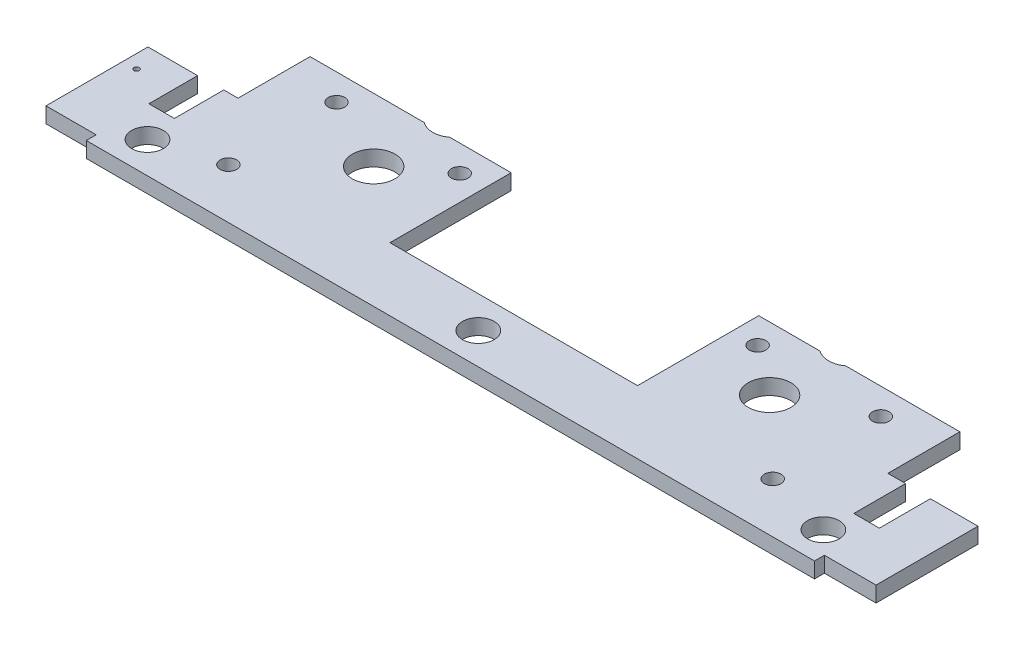
SolidWorks part; units mm, degrees
material "Copper"
ref_plane "Front Plane" through (0, 0, 0) normal (0, 0, 1) x (1, 0, 0)
ref_plane "Top Plane" through (0, 0, 0) normal (0, 1, 0) x (1, 0, 0)
ref_plane "Right Plane" through (0, 0, 0) normal (1, 0, 0) x (0, 0, -1)
sketch "Sketch1" plane through (0, 0, 0) normal (0, 1, 0) x (1, 0, 0)
  line L0 (44.3513, -40.0144) -> (37.1363, -40.0144)
  line L1 (0, 0) -> (0, -46.6159) construction
  line L2 (-19.6486, -28.7674) -> (44.3513, -28.7674) construction
  line L3 (-36.4337, -40.0144) -> (-36.4337, -46.6159)
  line L4 (37.1363, -40.0144) -> (37.1363, -46.6159)
  line L5 (-36.4337, -40.0144) -> (-43.6487, -40.0144)
  line L6 (-32.4727, -10.3704) -> (-32.4727, -29.6479)
  line L7 (-32.4727, 38.1938) -> (-32.4727, -29.6479) construction
  line L8 (-19.6486, -20.6394) -> (46.7444, -20.6394) construction
  line L9 (-42.3787, -29.6159) -> (-32.4727, -29.6479)
  line L10 (-12.1556, -10.3704) -> (-32.4727, -10.3704)
  line L11 (29.9683, -46.6159) -> (37.1363, -46.6159)
  line L12 (44.3513, -40.0144) -> (44.3513, -31.6519)
  line L13 (42.3513, -29.6159) -> (38.7463, -29.6159)
  line L14 (38.7463, -29.6159) -> (33.1753, -29.6479)
  line L15 (-11.5577, -34.6159) -> (-12.1556, -34.6159)
  line L16 (-12.1556, -34.6159) -> (-12.1556, -10.3704)
  line L17 (33.1753, -29.6479) -> (33.1753, 37.3661) construction
  line L18 (33.1753, -12.9294) -> (33.1753, -29.6479)
  line L19 (12.8581, -10.3704) -> (33.1753, -10.3704)
  line L20 (33.1753, -10.3704) -> (33.1753, -12.9294)
  line L21 (-43.6487, -29.6479) -> (-43.6487, -44.6339) construction
  line L22 (-43.6487, -30.8859) -> (-43.6487, -40.0144)
  line L23 (-36.4337, -46.6159) -> (-30.0837, -46.6159)
  line L24 (-30.0837, -46.6159) -> (29.9683, -46.6159)
  line L25 (-11.5577, -34.6159) -> (12.2603, -34.6159)
  line L26 (-19.6486, -28.7674) -> (-19.6486, -3.6898) construction
  line L27 (-19.6486, -3.6898) -> (-12.1556, -3.6898) construction
  line L28 (-43.6487, -30.8859) -> (-43.6487, -29.6479)
  line L29 (-43.6487, -29.6479) -> (-42.3787, -29.6159)
  line L30 (44.3513, -31.6519) -> (44.3513, -29.6159)
  line L31 (44.3513, -29.6159) -> (42.3513, -29.6159)
  line L32 (12.2603, -34.6159) -> (12.8581, -34.6159)
  line L33 (12.8581, -34.6159) -> (12.8581, -10.3704)
  circle A2 centre (-19.6486, -28.7674) radius 2.159
  circle A3 centre (-19.6486, -20.6394) radius 2.159
  circle A4 centre (20.3514, -20.6394) radius 2.159
  circle A5 centre (20.3514, -28.7674) radius 2.159
  dimension "D2" = 7.493
  dimension "D8" = 4.318
  dimension "D3" = 4.318
  dimension "D6" = 4.318
  dimension "D9" = 4.318
  dimension "D10" = 8.128
  dimension "D1" = 12
  dimension "D4" = 0
  dimension "D11" = 8.128
  dimension "D12" = 0
extrude "Boss-Extrude1" add sketch "Sketch1" along normal blind 1.575
sketch "Sketch2" plane through (0, 0, 0) normal (0, -1, 0) x (1, 0, 0)
  line L2 (-49.1064, 40.0144) -> (44.3513, 40.0144)
  line L4 (-49.1064, 40.0144) -> (-49.1064, 46.6164)
  line L6 (-49.1064, 46.6164) -> (44.3513, 46.6164)
  line L7 (44.3513, 40.0144) -> (44.3513, 46.6164)
  line L10 (-49.1064, 40.0144) -> (44.3513, 46.6164) construction
  line L12 (-49.1064, 46.6164) -> (44.3513, 40.0144) construction
  point P0 (-2.3775, 43.3154)
  dimension "D1" = 6.602
extrude "Cut-Extrude1" cut sketch "Sketch2" against normal through all
sketch "Sketch3" plane through (0, 0, 0) normal (0, -1, 0) x (1, 0, 0)
  line L0 (-41.5047, 40.0144) -> (-41.5047, 29.6188)
  line L1 (-43.6487, 40.0144) -> (44.3513, 40.0144) construction
  line L3 (-32.4727, 29.6479) -> (-42.3787, 29.6159) construction
  line L4 (-41.5047, 29.6188) -> (-34.6297, 29.641)
  line L8 (-41.5047, 40.0144) -> (-48.1288, 40.0144)
  line L9 (-48.1288, 40.0144) -> (-48.1288, 8.9761)
  line L10 (-48.1288, 8.9761) -> (-34.6297, 8.9761)
  line L11 (-34.6297, 29.641) -> (-34.6297, 8.9761)
  dimension "D1" = 6.6241
  dimension "D2" = 6.875
  dimension "D3" = 31.0383
  dimension "D4" = 20.6649
  dimension "D5" = 10.3956
extrude "Cut-Extrude2" cut sketch "Sketch3" against normal through all
sketch "Sketch4" plane through (0, 0, 0) normal (0, -1, 0) x (1, 0, 0)
  line L0 (42.3513, 40.0144) -> (42.3513, 32.4201)
  line L1 (35.4763, 29.6159) -> (35.4763, 10.3704)
  line L2 (35.4763, 10.3704) -> (54.7109, 10.3704)
  line L7 (54.7109, 10.3704) -> (54.7109, 40.0144)
  line L8 (-41.5047, 40.0144) -> (44.3513, 40.0144) construction
  line L11 (44.3513, 40.0144) -> (44.3513, 29.6159) construction
  line L12 (42.3513, 32.4201) -> (42.3513, 29.6159)
  line L13 (44.3513, 29.6159) -> (38.7463, 29.6159) construction
  line L14 (42.3513, 29.6159) -> (35.4763, 29.6159)
  line L15 (42.3513, 40.0144) -> (54.7109, 40.0144)
  dimension "D2" = 2
extrude "Cut-Extrude3" cut sketch "Sketch4" against normal through all
sketch "Sketch6" plane through (0, 0, 0) normal (0, -1, 0) x (-1, 0, 0)
  circle A0 centre (27.1416, -35.9479) radius 0.8382
  circle A1 centre (27.1416, -25.0259) radius 0.8382
  circle A2 centre (14.6956, -25.0259) radius 0.8382
  circle A3 centre (-15.3981, -25.0259) radius 0.8382
  circle A4 centre (-27.8444, -25.0259) radius 0.8382
  circle A5 centre (-27.8444, -35.9479) radius 0.8382
extrude "Cut-Extrude4" cut sketch "Sketch6" against normal blind 2.54
sketch "Sketch7" plane through (0, 0, 0) normal (0, -1, 0) x (1, 0, 0)
  line L0 (-32.4727, 10.3704) -> (-32.4727, 29.6479) construction
  line L1 (-32.4727, 22.3704) -> (33.1753, 22.3704)
  line L2 (-32.4727, 22.3704) -> (-32.4727, 10.3704)
  line L3 (-32.4727, 10.3704) -> (33.1753, 10.3704)
  line L4 (33.1753, 22.3704) -> (33.1753, 10.3704)
  dimension "D1" = 12
extrude "Cut-Extrude5" cut sketch "Sketch7" against normal through all
sketch "Sketch11" plane through (0, 1.575, 0) normal (0, 1, 0) x (1, 0, 0)
  circle A0 centre (-40.1444, -32.2238) radius 0.27
extrude "ID HOLE" cut sketch "Sketch11" against normal through all
sketch "Sketch12" plane through (0, 0, 0) normal (0, -1, 0) x (-1, 0, 0)
  line L0 (42.3787, -29.6159) -> (32.4727, -29.6479) construction
  line L1 (36.4887, -29.635) -> (33.9137, -29.635)
  line L2 (36.4887, -29.635) -> (36.4887, -34.635)
  line L3 (36.4887, -34.635) -> (33.9137, -34.635)
  line L4 (33.9137, -29.635) -> (33.9137, -34.635)
  dimension "D1" = 2.575
  dimension "D2" = 5
  dimension "D3" = 5.016
extrude "Notch for BPR (TOP VIEW)" cut sketch "Sketch12" against normal through all
sketch "Sketch14" plane through (0, 0, 0) normal (0, -1, 0) x (-1, 0, 0)
  line L1 (-42.3513, -40.0144) -> (-42.3513, -27.0505) construction
  line L2 (-33.1753, -22.3704) -> (-21.6417, -22.3704) construction
  line L4 (-34.9663, -34.873) -> (-37.5413, -34.873)
  line L5 (-34.9663, -34.873) -> (-34.9663, -22.3704)
  line L6 (-34.9663, -22.3704) -> (-37.5413, -22.3704)
  line L7 (-37.5413, -34.873) -> (-37.5413, -22.3704)
  dimension "D1" = 79.046
  dimension "D2" = 2.575
extrude "Notch for BPL (TOP VIEW)" cut sketch "Sketch14" against normal through all contours L5 L6 L7 L4
sketch "Sketch17" plane through (0, 0, 0) normal (0, -1, 0) x (1, 0, 0)
  line L0 (37.1363, 40.0144) -> (37.1363, 46.6159) construction
  line L1 (-36.4337, 40.0144) -> (37.1363, 40.0144)
  line L2 (-36.4337, 40.0144) -> (-36.4337, 41.0144)
  line L3 (-36.4337, 41.0144) -> (37.1363, 41.0144)
  line L4 (37.1363, 40.0144) -> (37.1363, 41.0144)
  dimension "D1" = 1
extrude "Create Lip for M3 Spacer Hole" add sketch "Sketch17" against normal blind 1.575
sketch "Sketch15" plane through (0, 0, 0) normal (0, -1, 0) x (1, 0, 0)
  line L0 (-2.4821, 41.0144) -> (2.1436, 41.0144) construction
  line L2 (37.1363, 41.0144) -> (-36.4337, 41.0144) construction
  line L3 (-2.17, 34.6159) -> (2.1436, 34.6159) construction
  line L6 (-11.5577, 34.6159) -> (12.2603, 34.6159) construction
  line L7 (0, 41.0144) -> (-0.0132, 34.6159) construction
  line L8 (0, 0) -> (0, 46.6159) construction
  line L9 (-0.0066, 37.8358) -> (2.1436, 37.8358) construction
  line L10 (-0.0066, 37.8358) -> (-1.1093, 37.8358) construction
  line L11 (-1000.0066, 37.8358) -> (48999.9934, 37.8358)
  circle A0 centre (-0.0066, 37.8358) radius 1.6
  circle A1 centre (-33.4297, 37.8358) radius 1.6
  circle A2 centre (34.8513, 37.8358) radius 1.6
  dimension "D1" = 3.2
  dimension "D2" = 3.2
  dimension "D4" = 3.2
  dimension "D3" = 3.004
  dimension "D5" = 7.5
extrude "HOLE for M3 Spacer" cut sketch "Sketch15" against normal through all
sketch "Sketch18" plane through (0, 0, 0) normal (0, -1, 0) x (1, 0, 0)
  line L0 (-41.5047, 29.6188) -> (-41.5047, 40.0144) construction
  line L1 (-36.4887, 29.6194) -> (-41.5047, 29.6194)
  line L2 (-36.4887, 29.6194) -> (-36.4887, 29.9194)
  line L3 (-36.4887, 29.9194) -> (-41.5047, 29.9194)
  line L4 (-41.5047, 29.6194) -> (-41.5047, 29.9194)
  line L5 (42.3513, 40.0144) -> (42.3513, 29.6159) construction
  line L6 (37.5413, 25.0144) -> (42.3513, 25.0144)
  line L7 (37.5413, 25.0144) -> (37.5413, 25.3144)
  line L8 (37.5413, 25.3144) -> (42.3513, 25.3144)
  line L9 (42.3513, 25.0144) -> (42.3513, 25.3144)
  dimension "D1" = 0.3
  dimension "D2" = 0.3
  dimension "D3" = 15
  dimension "D4" = 10.395
sketch "Sketch19" plane through (0, 0, 0) normal (0, -1, 0) x (1, 0, 0)
  line L1 (37.0403, 29.7144) -> (43.0542, 29.7144)
  line L2 (37.0403, 29.7144) -> (37.0403, 28.0144)
  line L3 (37.0403, 28.0144) -> (43.0542, 28.0144)
  line L4 (43.0542, 29.7144) -> (43.0542, 28.0144)
  line L5 (-45.4676, 29.7144) -> (-35.6531, 29.7144)
  line L6 (-45.4676, 29.7144) -> (-45.4676, 28.0144)
  line L7 (-45.4676, 28.0144) -> (-35.6531, 28.0144)
  line L8 (-35.6531, 29.7144) -> (-35.6531, 28.0144)
  dimension "D1" = 13
  dimension "D2" = 1.7
  dimension "D3" = 13
  dimension "D4" = 1.7
extrude "Cut-Extrude7" cut sketch "Sketch19" against normal through all
sketch "Sketch20" plane through (0, 0, 0) normal (0, -1, 0) x (-1, 0, 0)
  line L0 (-33.1881, -60.0458) -> (-33.1881, 49939.9542) construction
  line L1 (-12.8581, -34.6159) -> (-12.8581, -10.3704) construction
  line L4 (-30.3841, -54.1453) -> (-30.3841, 49945.8547) construction
  line L5 (-30.9861, -50.849) -> (-30.9861, -17.6227) construction
  line L6 (-32.5861, -44.8342) -> (-32.5861, -27.387) construction
  dimension "D1" = 20.33
  dimension "D2" = 17.526
  dimension "D3" = 2.804
  dimension "D4" = 18.128
  dimension "D5" = 1.6
  dimension "D6" = 19.728
sketch "Sketch21" plane through (0, 0, 0) normal (0, -1, 0) x (-1, 0, 0)
  line L0 (-20.3514, -20.6394) -> (-20.3514, -28.7674) construction
  line L1 (-12.8581, -34.6159) -> (-12.8581, -10.3704) construction
  dimension "D1" = 7.4933
sketch "Sketch22" plane through (0, 0, 0) normal (0, -1, 0) x (1, 0, 0)
  line L0 (-1020.7659, 23.6394) -> (48979.2341, 23.6394) construction
  line L1 (-1024.4065, 14.7494) -> (48975.5935, 14.7494) construction
  line L2 (-12.1556, 22.3704) -> (-12.1556, 14.7494)
  line L3 (-12.1556, 34.6159) -> (-12.1556, 10.3704) construction
  line L4 (-12.1556, 14.7494) -> (-32.4727, 14.7494)
  line L5 (-32.4727, 10.3704) -> (-32.4727, 29.6479) construction
  line L6 (-32.4727, 14.7494) -> (-32.4727, 22.3704)
  line L7 (-12.1556, 22.3704) -> (-12.1556, 23.6394)
  line L8 (-12.1556, 23.6394) -> (-32.4727, 23.6394)
  line L9 (-32.4727, 23.6394) -> (-32.4727, 22.3704)
  point P0 (-12.1556, 22.3704)
  point P11 (-32.4727, 22.3704)
  dimension "D1" = 3
  dimension "D2" = 8.89
extrude "Boss-Extrude2" [suppressed] add sketch "Sketch22" against normal blind 1.575
equation "\"D4@Sketch20\"=\"D2@Sketch20\"+.602mm"
